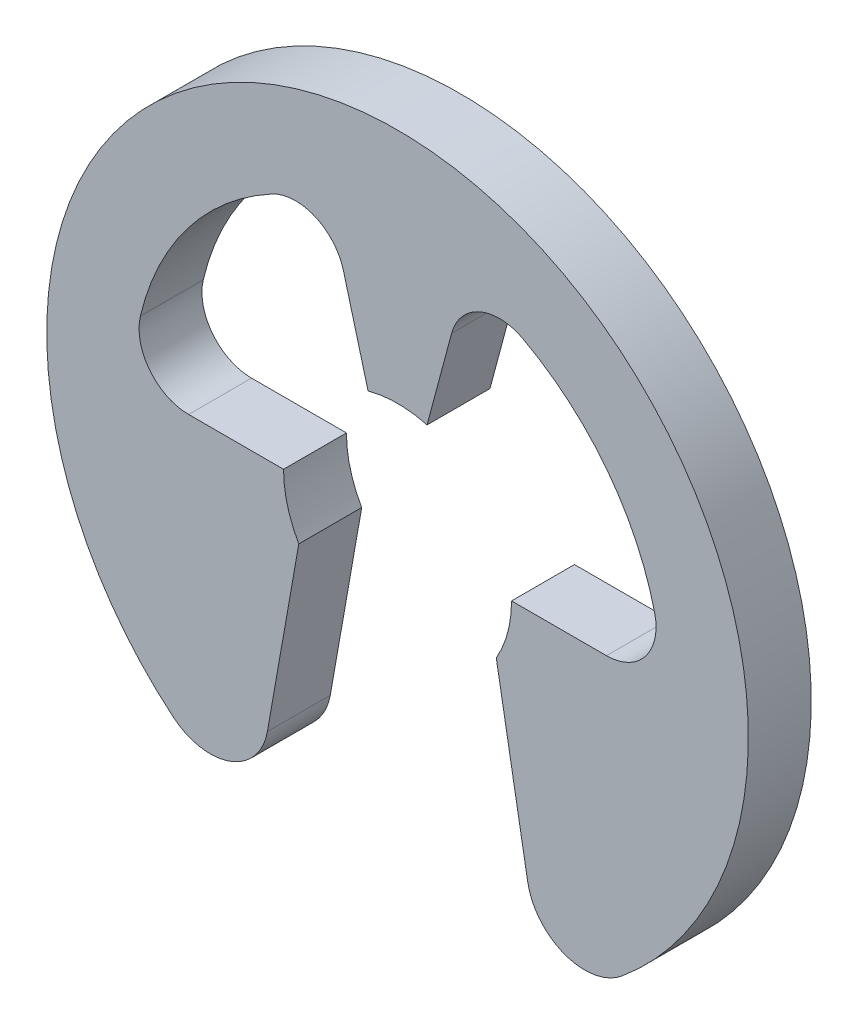
SolidWorks part; units mm, degrees
ref_plane "Plane1" through (0, 0, 0) normal (0, 0, 1) x (1, 0, 0)
ref_plane "Plane2" through (0, 0, 0) normal (0, 1, 0) x (1, 0, 0)
ref_plane "Plane3" through (0, 0, 0) normal (1, 0, 0) x (0, 0, -1)
sketch "Clipboard" plane through (0, 0, 0) normal (0, 0, 1) x (1, 0, 0)
  line L0 (0, 0) -> (0.55, 0)
  circle A0 centre (0, 0) radius 0.65
  circle A1 centre (0, 0) radius 2
  dimension "FreeID" = 1.3
  dimension "FreeOD" = 4
  dimension "Bridge" = 0.55
sketch "BodySke" plane through (0, 0, 0) normal (0, 0, 1) x (1, 0, 0)
  line L0 (-0.7581, 0) -> (0.7581, 0) construction
  line L1 (0, 0) -> (0, 0.725) construction
  line L2 (0, 0) -> (0.1962, 0.7323) construction
  line L3 (0, 0) -> (0.6279, -0.3625) construction
  line L4 (0, 0) -> (-0.1962, 0.7323) construction
  line L5 (0, 0) -> (-0.6279, -0.3625) construction
  line L6 (0.6279, -0.3625) -> (0.8277, -1.4959)
  line L7 (-0.6279, -0.3625) -> (-0.8277, -1.4959)
  line L9 (0.725, 0) -> (1.3284, 0)
  line L10 (-0.725, 0) -> (-1.3284, 0)
  line L11 (0.1876, 0.7003) -> (0.3438, 1.2832)
  line L12 (-0.1876, 0.7003) -> (-0.3438, 1.2832)
  circle A0 centre (0, 0) radius 0.725 construction
  arc A1 (1.6353, 0.3883) -> (0.7983, 1.4791) centre (0, 0) ccw
  arc A2 (1.4262, -1.7153) -> (-1.4262, -1.7153) centre (0, 0) ccw
  arc A3 (0.6279, -0.3625) -> (0.725, 0) centre (0, 0) ccw
  arc A4 (-0.7983, 1.4791) -> (-1.6353, 0.3883) centre (0, 0) ccw
  arc A5 (-0.725, 0) -> (-0.6279, -0.3625) centre (0, 0) ccw
  arc A6 (-0.1876, 0.7003) -> (0.1876, 0.7003) centre (0, 0) cw
  arc A7 (0.7983, 1.4791) -> (0.3438, 1.2832) centre (0.6485, 1.2015) ccw
  arc A8 (0.8277, -1.4959) -> (1.4262, -1.7153) centre (1.1906, -1.4319) ccw
  arc A9 (-1.4262, -1.7153) -> (-0.8277, -1.4959) centre (-1.1906, -1.4319) ccw
  arc A10 (-1.6353, 0.3883) -> (-1.3284, 0) centre (-1.3284, 0.3154) ccw
  arc A11 (-0.3438, 1.2832) -> (-0.7983, 1.4791) centre (-0.6485, 1.2015) ccw
  arc A12 (1.3284, 0) -> (1.6353, 0.3883) centre (1.3284, 0.3154) ccw
  dimension "D1" = 30
  dimension "GrooveDia" = 1.45
  dimension "OutsideDia" = 4.4615
  dimension "D3" = 30
  dimension "TipRad" = 0.3685
  dimension "CavityDia" = 3.3615
  dimension "CavityFilletRad" = 0.3154
  dimension "D4" = 20
extrude "Body" add sketch "BodySke" against normal blind 0.4
equation "' \"FreeID@Clipboard\" = 0.64"
equation "' \"Thickness@Body\" = 0.25"
equation "' \"GrooveDia@BodySke\" = 0.72"
equation "' \"FreeOD@Clipboard\" = 2"
equation "' \"Bridge@Clipboard\" = 0.3"
equation "' \"FreeID@Clipboard\" = 19.5"
equation "' \"Thickness@Body\" = 1.3"
equation "' \"GrooveDia@BodySke\" = 20.00"
equation "' \"FreeOD@Clipboard\" = 37.1"
equation "' \"Bridge@Clipboard\" = 3.3"
equation "\"OutsideDia@BodySke\" = ( \"GrooveDia@BodySke\"  /  \"FreeID@Clipboard\" )  * \"FreeOD@Clipboard\""
equation "\"CavityDia@BodySke\" = \"OutsideDia@BodySke\"  - 2 * \"Bridge@Clipboard\""
equation "\"CavityFilletRad@BodySke\" =  (\"CavityDia@BodySke\" - \"GrooveDia@BodySke\") / 2 * 0.33"
equation "\"TipRad@BodySke\" = 0.67 * \"Bridge@Clipboard\""
